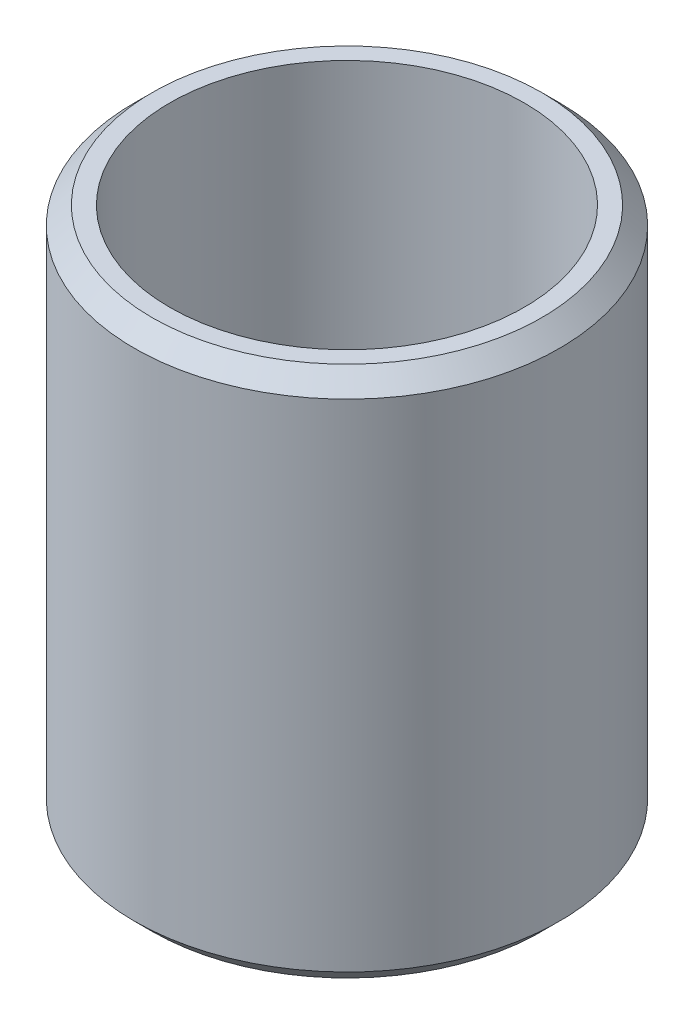
SolidWorks part; units mm, degrees
material "Chrome Stainless Steel"
ref_plane "Front Plane" through (0, 0, 0) normal (0, 0, 1) x (1, 0, 0)
ref_plane "Top Plane" through (0, 0, 0) normal (0, 1, 0) x (1, 0, 0)
ref_plane "Right Plane" through (0, 0, 0) normal (1, 0, 0) x (0, 0, -1)
sketch "Sketch1" plane through (0, 0, 0) normal (0, 1, 0) x (1, 0, 0)
  circle A0 centre (0, 0) radius 1.27
  circle A1 centre (0, 0) radius 1.524
  dimension "D1" = 2.54
  dimension "D2" = 3.048
extrude "Boss-Extrude1" add sketch "Sketch1" along normal blind 3.81
chamfer "Chamfer1" distance 0.127 distance2 0.127 2 edges at (0, 0, 1.524) (0, 3.81, 1.524)
